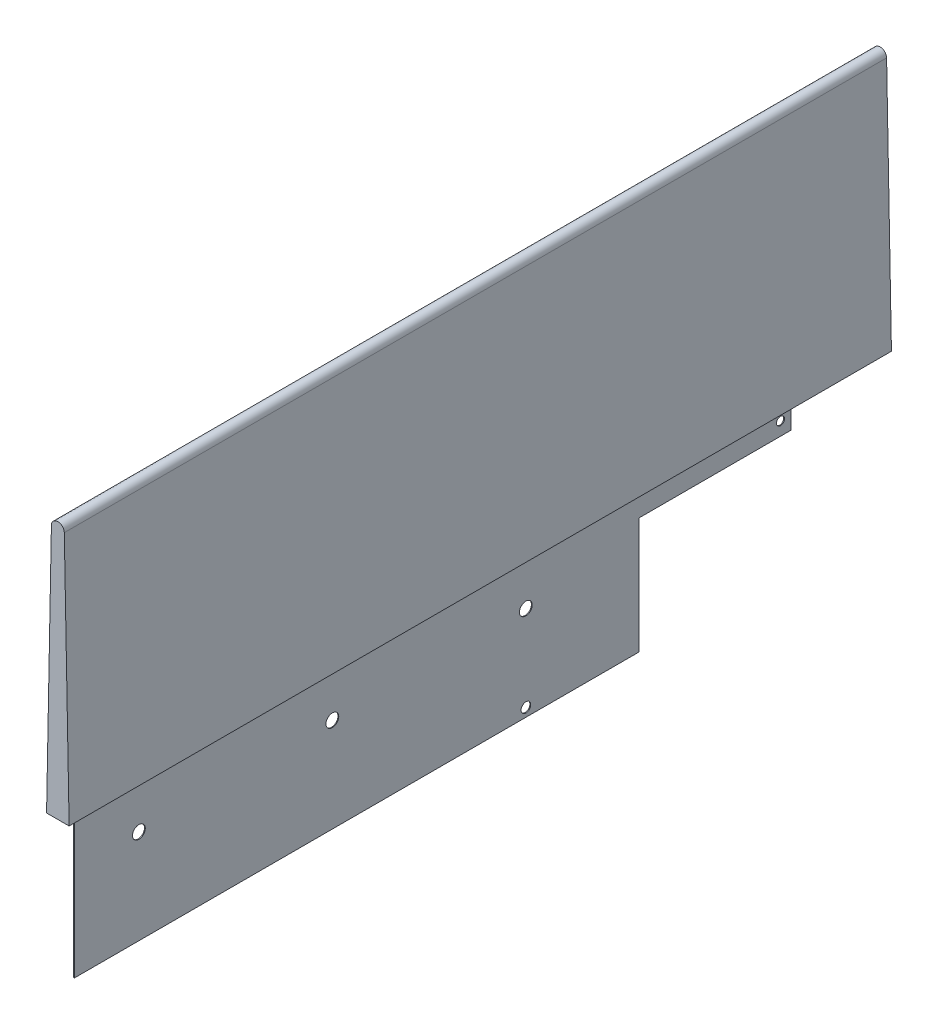
SolidWorks part; units mm, degrees
ref_plane "정면" through (0, 0, 0) normal (0, 0, 1) x (1, 0, 0)
ref_plane "윗면" through (0, 0, 0) normal (0, 1, 0) x (1, 0, 0)
ref_plane "우측면" through (0, 0, 0) normal (1, 0, 0) x (0, 0, -1)
sketch "스케치1" plane through (0, 0, 0) normal (0, 0, 1) x (1, 0, 0)
  line L0 (-3.5, 0) -> (3.5, 0)
  line L1 (0, 0) -> (0, 80)
  line L2 (-2, 78.0381) -> (-3.5, 0)
  line L3 (2, 78.0381) -> (3.5, 0)
  arc A0 (2, 78.0381) -> (-2, 78.0381) centre (0, 77.9996) ccw
  dimension "D1" = 3.5
  dimension "D2" = 80
  dimension "D3" = 2
extrude "보스-돌출1" add sketch "스케치1" against normal blind 110 and the other way blind 145 contours L1 A0 L2 L0 | L3 A0 L1 L0
ref_plane "평면1" through (0, 0, 0) normal (1, 0, 0) x (0, 0, -1)
sketch "스케치3" plane through (0, 0, 0) normal (1, 0, 0) x (0, 0, -1)
  line L2 (-140, 6) -> (-140, -45)
  line L88 (110, 78.0381) -> (110, 0) construction
  line L167 (110, 6) -> (110, -45)
  line L168 (-140, -45) -> (110, -45)
  line L173 (-140, 6) -> (110, 6)
  line L262 (90, -9) -> (90, 6)
  line L283 (110, -45) -> (35.0194, -45)
  line L284 (110, -45) -> (110, -9)
  line L289 (110, -9) -> (35.0194, -9)
  line L310 (35.0194, -45) -> (35.0194, -9)
  line L469 (-140, 6) -> (-140, -45)
  circle A20 centre (-60, -15.7836) radius 1.985
  circle A21 centre (0, -15.7836) radius 1.985
  circle A22 centre (-120, -15.7836) radius 1.985
  dimension "D10" = 15
  dimension "D29" = 3.97
  dimension "D30" = 3.97
  dimension "D31" = 3.97
  dimension "D6" = 20
  dimension "D1" = 250
  dimension "D4" = 51
  dimension "D28" = 6
  dimension "D32" = 60
  dimension "D33" = 60
extrude "보스-돌출2" add sketch "스케치3" along normal mid plane 0.254 separate body
sketch "스케치5" plane through (0, 0, 0) normal (1, 0, 0) x (0, 0, -1)
  line L4 (35.0194, -45) -> (35.0194, -9) construction
  circle A1 centre (0.0194, -42.3344) radius 1.5
  circle A2 centre (78.9615, -4.8953) radius 1.25
  point P0 (0, 0)
  dimension "D1" = 3
  dimension "D2" = 2.5
  dimension "D3" = 35
extrude "컷-돌출1" cut sketch "스케치5" against normal through all both and the other way through all
sketch "스케치6" plane through (-0.127, 0, 0) normal (-1, 0, 0) x (0, 0, 1)
  line L1 (-90, -9) -> (-82.3, -9)
  line L2 (-90, -9) -> (-90, 0)
  line L3 (-90, 0) -> (-82.3, 0)
  line L4 (-82.3, -9) -> (-82.3, 0)
  dimension "D1" = 7.7
extrude "컷-돌출2" cut sketch "스케치6" against normal through all
sketch "스케치7" plane through (-0.127, 0, 0) normal (-1, 0, 0) x (0, 0, 1)
  line L0 (-87.2733, 4.184) -> (-77.2733, 4.184) construction
  line L1 (-87.2733, 4.884) -> (-77.2733, 4.884)
  line L2 (-87.2733, 3.484) -> (-77.2733, 3.484)
  line L3 (-82.0285, 1.6907) -> (-72.0285, 1.6907) construction
  line L4 (-82.0285, 2.3907) -> (-72.0285, 2.3907)
  line L5 (-82.0285, 0.9907) -> (-72.0285, 0.9907)
  line L6 (-72.2733, 4.184) -> (-62.2733, 4.184) construction
  line L7 (-72.2733, 4.884) -> (-62.2733, 4.884)
  line L8 (-72.2733, 3.484) -> (-62.2733, 3.484)
  line L9 (-67.0285, 1.6907) -> (-57.0285, 1.6907) construction
  line L10 (-67.0285, 2.3907) -> (-57.0285, 2.3907)
  line L11 (-67.0285, 0.9907) -> (-57.0285, 0.9907)
  line L12 (-57.2733, 4.184) -> (-47.2733, 4.184) construction
  line L13 (-57.2733, 4.884) -> (-47.2733, 4.884)
  line L14 (-57.2733, 3.484) -> (-47.2733, 3.484)
  line L15 (-52.0285, 1.6907) -> (-42.0285, 1.6907) construction
  line L16 (-52.0285, 2.3907) -> (-42.0285, 2.3907)
  line L17 (-52.0285, 0.9907) -> (-42.0285, 0.9907)
  line L18 (-42.2733, 4.184) -> (-32.2733, 4.184) construction
  line L19 (-42.2733, 4.884) -> (-32.2733, 4.884)
  line L20 (-42.2733, 3.484) -> (-32.2733, 3.484)
  line L21 (-37.0285, 1.6907) -> (-27.0285, 1.6907) construction
  line L22 (-37.0285, 2.3907) -> (-27.0285, 2.3907)
  line L23 (-37.0285, 0.9907) -> (-27.0285, 0.9907)
  line L24 (-27.2733, 4.184) -> (-17.2733, 4.184) construction
  line L25 (-27.2733, 4.884) -> (-17.2733, 4.884)
  line L26 (-27.2733, 3.484) -> (-17.2733, 3.484)
  line L27 (-22.0285, 1.6907) -> (-12.0285, 1.6907) construction
  line L28 (-22.0285, 2.3907) -> (-12.0285, 2.3907)
  line L29 (-22.0285, 0.9907) -> (-12.0285, 0.9907)
  line L30 (-12.2733, 4.184) -> (-2.2733, 4.184) construction
  line L31 (-12.2733, 4.884) -> (-2.2733, 4.884)
  line L32 (-12.2733, 3.484) -> (-2.2733, 3.484)
  line L33 (-7.0285, 1.6907) -> (2.9715, 1.6907) construction
  line L34 (-7.0285, 2.3907) -> (2.9715, 2.3907)
  line L35 (-7.0285, 0.9907) -> (2.9715, 0.9907)
  line L36 (2.7267, 4.184) -> (12.7267, 4.184) construction
  line L37 (2.7267, 4.884) -> (12.7267, 4.884)
  line L38 (2.7267, 3.484) -> (12.7267, 3.484)
  line L39 (7.9715, 1.6907) -> (17.9715, 1.6907) construction
  line L40 (7.9715, 2.3907) -> (17.9715, 2.3907)
  line L41 (7.9715, 0.9907) -> (17.9715, 0.9907)
  line L42 (17.7267, 4.184) -> (27.7267, 4.184) construction
  line L43 (17.7267, 4.884) -> (27.7267, 4.884)
  line L44 (17.7267, 3.484) -> (27.7267, 3.484)
  line L45 (22.9715, 1.6907) -> (32.9715, 1.6907) construction
  line L46 (22.9715, 2.3907) -> (32.9715, 2.3907)
  line L47 (22.9715, 0.9907) -> (32.9715, 0.9907)
  line L48 (32.7267, 4.184) -> (42.7267, 4.184) construction
  line L49 (32.7267, 4.884) -> (42.7267, 4.884)
  line L50 (32.7267, 3.484) -> (42.7267, 3.484)
  line L51 (37.9715, 1.6907) -> (47.9715, 1.6907) construction
  line L52 (37.9715, 2.3907) -> (47.9715, 2.3907)
  line L53 (37.9715, 0.9907) -> (47.9715, 0.9907)
  line L54 (47.7267, 4.184) -> (57.7267, 4.184) construction
  line L55 (47.7267, 4.884) -> (57.7267, 4.884)
  line L56 (47.7267, 3.484) -> (57.7267, 3.484)
  line L57 (52.9715, 1.6907) -> (62.9715, 1.6907) construction
  line L58 (52.9715, 2.3907) -> (62.9715, 2.3907)
  line L59 (52.9715, 0.9907) -> (62.9715, 0.9907)
  line L60 (62.7267, 4.184) -> (72.7267, 4.184) construction
  line L61 (62.7267, 4.884) -> (72.7267, 4.884)
  line L62 (62.7267, 3.484) -> (72.7267, 3.484)
  line L63 (67.9715, 1.6907) -> (77.9715, 1.6907) construction
  line L64 (67.9715, 2.3907) -> (77.9715, 2.3907)
  line L65 (67.9715, 0.9907) -> (77.9715, 0.9907)
  line L66 (77.7267, 4.184) -> (87.7267, 4.184) construction
  line L67 (77.7267, 4.884) -> (87.7267, 4.884)
  line L68 (77.7267, 3.484) -> (87.7267, 3.484)
  line L69 (82.9715, 1.6907) -> (92.9715, 1.6907) construction
  line L70 (82.9715, 2.3907) -> (92.9715, 2.3907)
  line L71 (82.9715, 0.9907) -> (92.9715, 0.9907)
  line L72 (92.7267, 4.184) -> (102.7267, 4.184) construction
  line L73 (92.7267, 4.884) -> (102.7267, 4.884)
  line L74 (92.7267, 3.484) -> (102.7267, 3.484)
  line L75 (97.9715, 1.6907) -> (107.9715, 1.6907) construction
  line L76 (97.9715, 2.3907) -> (107.9715, 2.3907)
  line L77 (97.9715, 0.9907) -> (107.9715, 0.9907)
  line L78 (107.7267, 4.184) -> (117.7267, 4.184) construction
  line L79 (107.7267, 4.884) -> (117.7267, 4.884)
  line L80 (107.7267, 3.484) -> (117.7267, 3.484)
  line L81 (112.9715, 1.6907) -> (122.9715, 1.6907) construction
  line L82 (112.9715, 2.3907) -> (122.9715, 2.3907)
  line L83 (112.9715, 0.9907) -> (122.9715, 0.9907)
  line L84 (122.7267, 4.184) -> (132.7267, 4.184) construction
  line L85 (122.7267, 4.884) -> (132.7267, 4.884)
  line L86 (122.7267, 3.484) -> (132.7267, 3.484)
  line L87 (127.9715, 1.6907) -> (137.9715, 1.6907) construction
  line L88 (127.9715, 2.3907) -> (137.9715, 2.3907)
  line L89 (127.9715, 0.9907) -> (137.9715, 0.9907)
  arc A0 (-87.2733, 4.884) -> (-87.2733, 3.484) centre (-87.2733, 4.184) ccw
  arc A1 (-77.2733, 3.484) -> (-77.2733, 4.884) centre (-77.2733, 4.184) ccw
  arc A2 (-82.0285, 2.3907) -> (-82.0285, 0.9907) centre (-82.0285, 1.6907) ccw
  arc A3 (-72.0285, 0.9907) -> (-72.0285, 2.3907) centre (-72.0285, 1.6907) ccw
  arc A4 (-72.2733, 4.884) -> (-72.2733, 3.484) centre (-72.2733, 4.184) ccw
  arc A5 (-62.2733, 3.484) -> (-62.2733, 4.884) centre (-62.2733, 4.184) ccw
  arc A6 (-67.0285, 2.3907) -> (-67.0285, 0.9907) centre (-67.0285, 1.6907) ccw
  arc A7 (-57.0285, 0.9907) -> (-57.0285, 2.3907) centre (-57.0285, 1.6907) ccw
  arc A8 (-57.2733, 4.884) -> (-57.2733, 3.484) centre (-57.2733, 4.184) ccw
  arc A9 (-47.2733, 3.484) -> (-47.2733, 4.884) centre (-47.2733, 4.184) ccw
  arc A10 (-52.0285, 2.3907) -> (-52.0285, 0.9907) centre (-52.0285, 1.6907) ccw
  arc A11 (-42.0285, 0.9907) -> (-42.0285, 2.3907) centre (-42.0285, 1.6907) ccw
  arc A12 (-42.2733, 4.884) -> (-42.2733, 3.484) centre (-42.2733, 4.184) ccw
  arc A13 (-32.2733, 3.484) -> (-32.2733, 4.884) centre (-32.2733, 4.184) ccw
  arc A14 (-37.0285, 2.3907) -> (-37.0285, 0.9907) centre (-37.0285, 1.6907) ccw
  arc A15 (-27.0285, 0.9907) -> (-27.0285, 2.3907) centre (-27.0285, 1.6907) ccw
  arc A16 (-27.2733, 4.884) -> (-27.2733, 3.484) centre (-27.2733, 4.184) ccw
  arc A17 (-17.2733, 3.484) -> (-17.2733, 4.884) centre (-17.2733, 4.184) ccw
  arc A18 (-22.0285, 2.3907) -> (-22.0285, 0.9907) centre (-22.0285, 1.6907) ccw
  arc A19 (-12.0285, 0.9907) -> (-12.0285, 2.3907) centre (-12.0285, 1.6907) ccw
  arc A20 (-12.2733, 4.884) -> (-12.2733, 3.484) centre (-12.2733, 4.184) ccw
  arc A21 (-2.2733, 3.484) -> (-2.2733, 4.884) centre (-2.2733, 4.184) ccw
  arc A22 (-7.0285, 2.3907) -> (-7.0285, 0.9907) centre (-7.0285, 1.6907) ccw
  arc A23 (2.9715, 0.9907) -> (2.9715, 2.3907) centre (2.9715, 1.6907) ccw
  arc A24 (2.7267, 4.884) -> (2.7267, 3.484) centre (2.7267, 4.184) ccw
  arc A25 (12.7267, 3.484) -> (12.7267, 4.884) centre (12.7267, 4.184) ccw
  arc A26 (7.9715, 2.3907) -> (7.9715, 0.9907) centre (7.9715, 1.6907) ccw
  arc A27 (17.9715, 0.9907) -> (17.9715, 2.3907) centre (17.9715, 1.6907) ccw
  arc A28 (17.7267, 4.884) -> (17.7267, 3.484) centre (17.7267, 4.184) ccw
  arc A29 (27.7267, 3.484) -> (27.7267, 4.884) centre (27.7267, 4.184) ccw
  arc A30 (22.9715, 2.3907) -> (22.9715, 0.9907) centre (22.9715, 1.6907) ccw
  arc A31 (32.9715, 0.9907) -> (32.9715, 2.3907) centre (32.9715, 1.6907) ccw
  arc A32 (32.7267, 4.884) -> (32.7267, 3.484) centre (32.7267, 4.184) ccw
  arc A33 (42.7267, 3.484) -> (42.7267, 4.884) centre (42.7267, 4.184) ccw
  arc A34 (37.9715, 2.3907) -> (37.9715, 0.9907) centre (37.9715, 1.6907) ccw
  arc A35 (47.9715, 0.9907) -> (47.9715, 2.3907) centre (47.9715, 1.6907) ccw
  arc A36 (47.7267, 4.884) -> (47.7267, 3.484) centre (47.7267, 4.184) ccw
  arc A37 (57.7267, 3.484) -> (57.7267, 4.884) centre (57.7267, 4.184) ccw
  arc A38 (52.9715, 2.3907) -> (52.9715, 0.9907) centre (52.9715, 1.6907) ccw
  arc A39 (62.9715, 0.9907) -> (62.9715, 2.3907) centre (62.9715, 1.6907) ccw
  arc A40 (62.7267, 4.884) -> (62.7267, 3.484) centre (62.7267, 4.184) ccw
  arc A41 (72.7267, 3.484) -> (72.7267, 4.884) centre (72.7267, 4.184) ccw
  arc A42 (67.9715, 2.3907) -> (67.9715, 0.9907) centre (67.9715, 1.6907) ccw
  arc A43 (77.9715, 0.9907) -> (77.9715, 2.3907) centre (77.9715, 1.6907) ccw
  arc A44 (77.7267, 4.884) -> (77.7267, 3.484) centre (77.7267, 4.184) ccw
  arc A45 (87.7267, 3.484) -> (87.7267, 4.884) centre (87.7267, 4.184) ccw
  arc A46 (82.9715, 2.3907) -> (82.9715, 0.9907) centre (82.9715, 1.6907) ccw
  arc A47 (92.9715, 0.9907) -> (92.9715, 2.3907) centre (92.9715, 1.6907) ccw
  arc A48 (92.7267, 4.884) -> (92.7267, 3.484) centre (92.7267, 4.184) ccw
  arc A49 (102.7267, 3.484) -> (102.7267, 4.884) centre (102.7267, 4.184) ccw
  arc A50 (97.9715, 2.3907) -> (97.9715, 0.9907) centre (97.9715, 1.6907) ccw
  arc A51 (107.9715, 0.9907) -> (107.9715, 2.3907) centre (107.9715, 1.6907) ccw
  arc A52 (107.7267, 4.884) -> (107.7267, 3.484) centre (107.7267, 4.184) ccw
  arc A53 (117.7267, 3.484) -> (117.7267, 4.884) centre (117.7267, 4.184) ccw
  arc A54 (112.9715, 2.3907) -> (112.9715, 0.9907) centre (112.9715, 1.6907) ccw
  arc A55 (122.9715, 0.9907) -> (122.9715, 2.3907) centre (122.9715, 1.6907) ccw
  arc A56 (122.7267, 4.884) -> (122.7267, 3.484) centre (122.7267, 4.184) ccw
  arc A57 (132.7267, 3.484) -> (132.7267, 4.884) centre (132.7267, 4.184) ccw
  arc A58 (127.9715, 2.3907) -> (127.9715, 0.9907) centre (127.9715, 1.6907) ccw
  arc A59 (137.9715, 0.9907) -> (137.9715, 2.3907) centre (137.9715, 1.6907) ccw
  point P2 (-82.2733, 4.184)
  point P12 (-77.0285, 1.6907)
  point P18 (-67.2733, 4.184)
  point P25 (-62.0285, 1.6907)
  point P32 (-52.2733, 4.184)
  point P39 (-47.0285, 1.6907)
  point P46 (-37.2733, 4.184)
  point P53 (-32.0285, 1.6907)
  point P60 (-22.2733, 4.184)
  point P67 (-17.0285, 1.6907)
  point P74 (-7.2733, 4.184)
  point P81 (-2.0285, 1.6907)
  point P88 (7.7267, 4.184)
  point P95 (12.9715, 1.6907)
  point P102 (22.7267, 4.184)
  point P109 (27.9715, 1.6907)
  point P116 (37.7267, 4.184)
  point P123 (42.9715, 1.6907)
  point P130 (52.7267, 4.184)
  point P137 (57.9715, 1.6907)
  point P144 (67.7267, 4.184)
  point P151 (72.9715, 1.6907)
  point P158 (82.7267, 4.184)
  point P165 (87.9715, 1.6907)
  point P172 (97.7267, 4.184)
  point P179 (102.9715, 1.6907)
  point P186 (112.7267, 4.184)
  point P193 (117.9715, 1.6907)
  point P200 (127.7267, 4.184)
  point P207 (132.9715, 1.6907)
  dimension "D1" = 0.7
  dimension "D3" = 0.7
  dimension "D2" = 10
  dimension "D4" = 10
  dimension "D5" = 15
extrude "컷-돌출3" cut sketch "스케치7" against normal up to surface (0.254 mm away) up to face at (0.127, -12, -16.8299)
